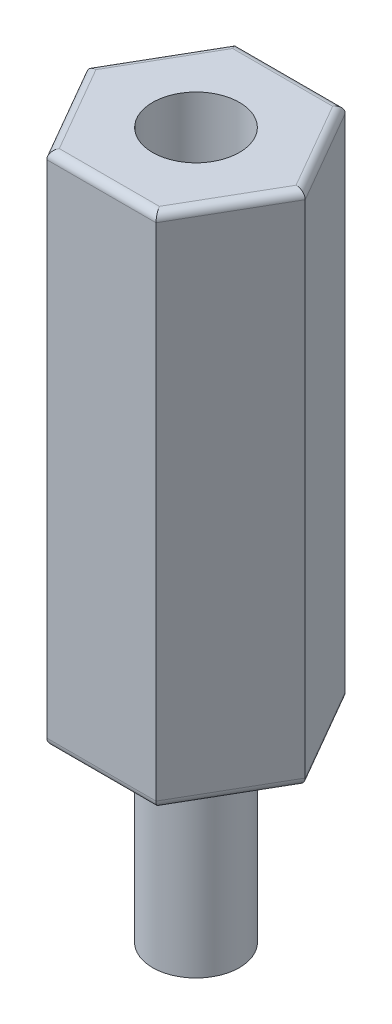
SolidWorks part; units mm, degrees
material "201.0-T43 Molde de fundição com isolamento (SS)"
ref_plane "Plano frontal" through (0, 0, 0) normal (0, 0, 1) x (1, 0, 0)
ref_plane "Plano superior" through (0, 0, 0) normal (0, 1, 0) x (1, 0, 0)
ref_plane "Plano direito" through (0, 0, 0) normal (1, 0, 0) x (0, 0, -1)
sketch "Esboço1" plane through (0, 0, 0) normal (0, 1, 0) x (1, 0, 0)
  line L1 (2.7482, 0) -> (1.3741, 2.38)
  line L2 (1.3741, 2.38) -> (-1.3741, 2.38)
  line L3 (-1.3741, 2.38) -> (-2.7482, 0)
  line L4 (-2.7482, 0) -> (-1.3741, -2.38)
  line L5 (-1.3741, -2.38) -> (1.3741, -2.38)
  line L6 (1.3741, -2.38) -> (2.7482, 0)
  circle A0 centre (0, 0) radius 2.38 construction
  dimension "D1" = 4.76
extrude "Ressalto-extrusão1" add sketch "Esboço1" along normal blind 13
fillet "Filete1" radius 0.2 12 edges at (0, 13, -2.38) (-2.0611, 13, -1.19) (-2.0611, 13, 1.19) (0, 13, 2.38) (2.0611, 13, 1.19) (2.0611, 13, -1.19) (0, 0, 2.38) (-2.0611, 0, 1.19) (-2.0611, 0, -1.19) (0, 0, -2.38) (2.0611, 0, -1.19) (2.0611, 0, 1.19)
sketch "Esboço2" plane through (0, 0, 0) normal (0, -1, 0) x (1, 0, 0)
  circle A0 centre (0, 0) radius 1.0922
  dimension "D1" = 2.1844
extrude "Ressalto-extrusão2" add sketch "Esboço2" along normal blind 4.76
sketch "Esboço3" plane through (0, 13, 0) normal (0, 1, 0) x (1, 0, 0)
  circle A0 centre (0, 0) radius 1.0922
extrude "Corte-extrusão1" cut sketch "Esboço3" against normal blind 4.76
